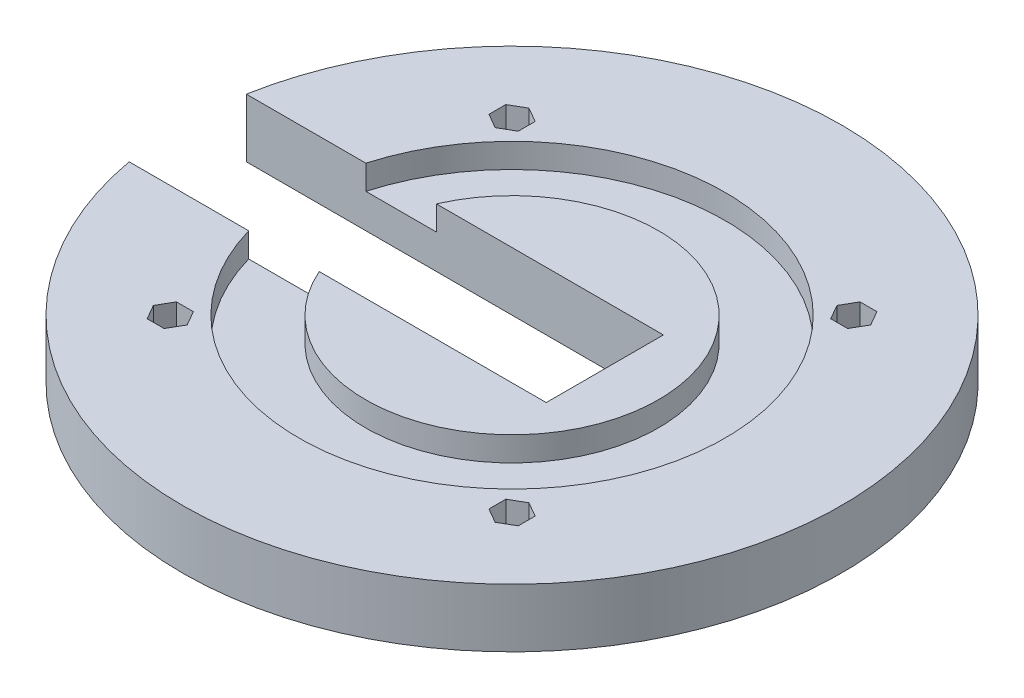
SolidWorks part; units mm, degrees
material "1.0503 (C45)"
ref_plane "前视基准面" through (0, 0, 0) normal (0, 0, 1) x (1, 0, 0)
ref_plane "上视基准面" through (0, 0, 0) normal (0, 1, 0) x (1, 0, 0)
ref_plane "右视基准面" through (0, 0, 0) normal (1, 0, 0) x (0, 0, -1)
sketch "草图1" plane through (0, 0, 0) normal (0, 1, 0) x (1, 0, 0)
  circle A0 centre (0, 0) radius 67.5
  dimension "D1" = 135
extrude "凸台-拉伸1" add sketch "草图1" along normal blind 12
sketch "草图2" plane through (0, 12, 0) normal (0, 1, 0) x (1, 0, 0)
  line L0 (-67.5, 0) -> (67.5, 0) construction
  line L2 (-41, -12) -> (19, -12)
  line L3 (-41, -12) -> (-41, 12)
  line L4 (-41, 12) -> (19, 12)
  line L5 (19, -12) -> (19, 12)
  line L6 (-41, -12) -> (19, 12) construction
  line L7 (-41, 12) -> (19, -12) construction
  circle A0 centre (0, 0) radius 67.5 construction
  point P5 (-11, 0)
  dimension "D1" = 24
  dimension "D2" = 60
  dimension "D3" = 19
extrude "切除-拉伸1" cut sketch "草图2" against normal through all
sketch "草图3" plane through (0, 0, 0) normal (1, 0, 0) x (0, 0, -1)
  line L0 (0, 0) -> (0, 61.3027) construction
  line L2 (-5, 0) -> (5, 0)
  line L3 (-5, 0) -> (-5, 15)
  line L4 (-5, 15) -> (5, 15)
  line L5 (5, 0) -> (5, 15)
  line L6 (-5, 0) -> (5, 15) construction
  line L7 (-5, 15) -> (5, 0) construction
  line L8 (-67.5, 0) -> (67.5, 0) construction
  point P3 (0, 7.5)
  dimension "D1" = 15
  dimension "D2" = 10
extrude "切除-拉伸2" [suppressed] cut sketch "草图3" along normal blind 97
sketch "草图4" plane through (0, 12, 0) normal (0, 1, 0) x (1, 0, 0)
  line L0 (0, 0) -> (35.0018, 35.0018) construction
  line L1 (35.0018, -38.4659) -> (38.0018, -36.7338)
  line L2 (38.4659, 35.0018) -> (36.7338, 38.0018)
  line L3 (36.7338, 38.0018) -> (33.2697, 38.0018)
  line L4 (33.2697, 38.0018) -> (31.5377, 35.0018)
  line L5 (31.5377, 35.0018) -> (33.2697, 32.0018)
  line L6 (33.2697, 32.0018) -> (36.7338, 32.0018)
  line L7 (36.7338, 32.0018) -> (38.4659, 35.0018)
  line L8 (38.0018, -36.7338) -> (38.0018, -33.2697)
  line L9 (38.0018, -33.2697) -> (35.0018, -31.5377)
  line L10 (35.0018, -31.5377) -> (32.0018, -33.2697)
  line L11 (32.0018, -33.2697) -> (32.0018, -36.7338)
  line L12 (32.0018, -36.7338) -> (35.0018, -38.4659)
  line L13 (-38.4659, -35.0018) -> (-36.7338, -38.0018)
  line L14 (-36.7338, -38.0018) -> (-33.2697, -38.0018)
  line L15 (-33.2697, -38.0018) -> (-31.5377, -35.0018)
  line L16 (-31.5377, -35.0018) -> (-33.2697, -32.0018)
  line L17 (-33.2697, -32.0018) -> (-36.7338, -32.0018)
  line L18 (-36.7338, -32.0018) -> (-38.4659, -35.0018)
  line L19 (-35.0018, 38.4659) -> (-38.0018, 36.7338)
  line L20 (-38.0018, 36.7338) -> (-38.0018, 33.2697)
  line L21 (-38.0018, 33.2697) -> (-35.0018, 31.5377)
  line L22 (-35.0018, 31.5377) -> (-32.0018, 33.2697)
  line L23 (-32.0018, 33.2697) -> (-32.0018, 36.7338)
  line L24 (-32.0018, 36.7338) -> (-35.0018, 38.4659)
  circle A4 centre (35.0018, 35.0018) radius 3 construction
  point P13 (0, 0)
  point P32 (0, 0)
  dimension "D2" = 6
  dimension "D1" = 49.5
  dimension "D3" = 4
extrude "切除-拉伸3" cut sketch "草图4" against normal through all
sketch "草图5" plane through (0, 12, 0) normal (0, 1, 0) x (1, 0, 0)
  line L0 (0, 0) -> (38.625, 0) construction
  circle A0 centre (38.625, 0) radius 5 construction
  circle A1 centre (0, 0) radius 30
  circle A2 centre (0, 0) radius 43.625
  dimension "D2" = 10
  dimension "D3" = 60
  dimension "D1" = 38.625
extrude "切除-拉伸4" cut sketch "草图5" against normal blind 5
sketch "草图6" plane through (0, 12, 0) normal (0, 1, 0) x (1, 0, 0)
  line L0 (-27.4955, -12) -> (-41, -12) construction
  line L1 (-41, 12) -> (-116.0675, 12)
  line L2 (-41, 12) -> (-41, -12)
  line L3 (-41, -12) -> (-116.0675, -12)
  line L4 (-116.0675, 12) -> (-116.0675, -12)
extrude "切除-拉伸5" cut sketch "草图6" against normal through all
